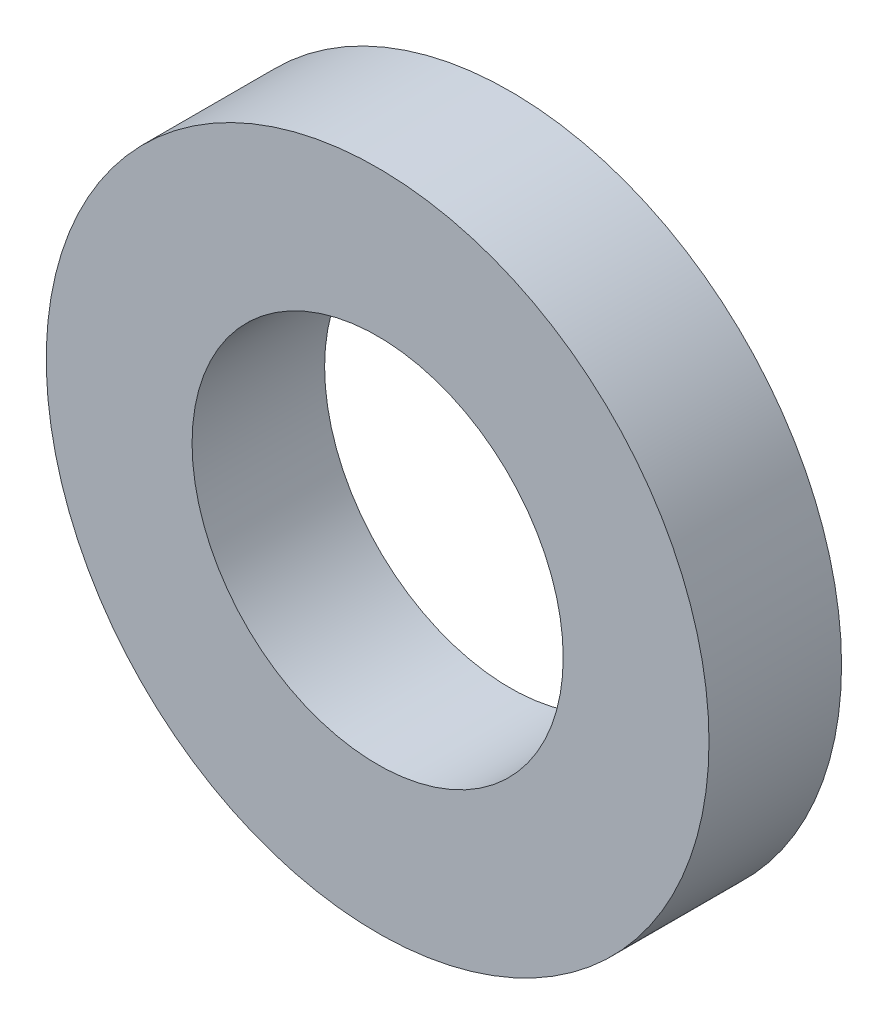
SolidWorks part; units mm, degrees
ref_plane "Front Plane" through (0, 0, 0) normal (0, 0, 1) x (1, 0, 0)
ref_plane "Top Plane" through (0, 0, 0) normal (0, 1, 0) x (1, 0, 0)
ref_plane "Right Plane" through (0, 0, 0) normal (1, 0, 0) x (0, 0, -1)
sketch "Sketch2" plane through (0, 0, 0) normal (0, 0, 1) x (1, 0, 0)
  circle A0 centre (0, 0) radius 140
  circle A1 centre (0, 0) radius 250
  dimension "D1" = 280
  dimension "D2" = 500
extrude "Boss-Extrude1" add sketch "Sketch2" along normal blind 100
